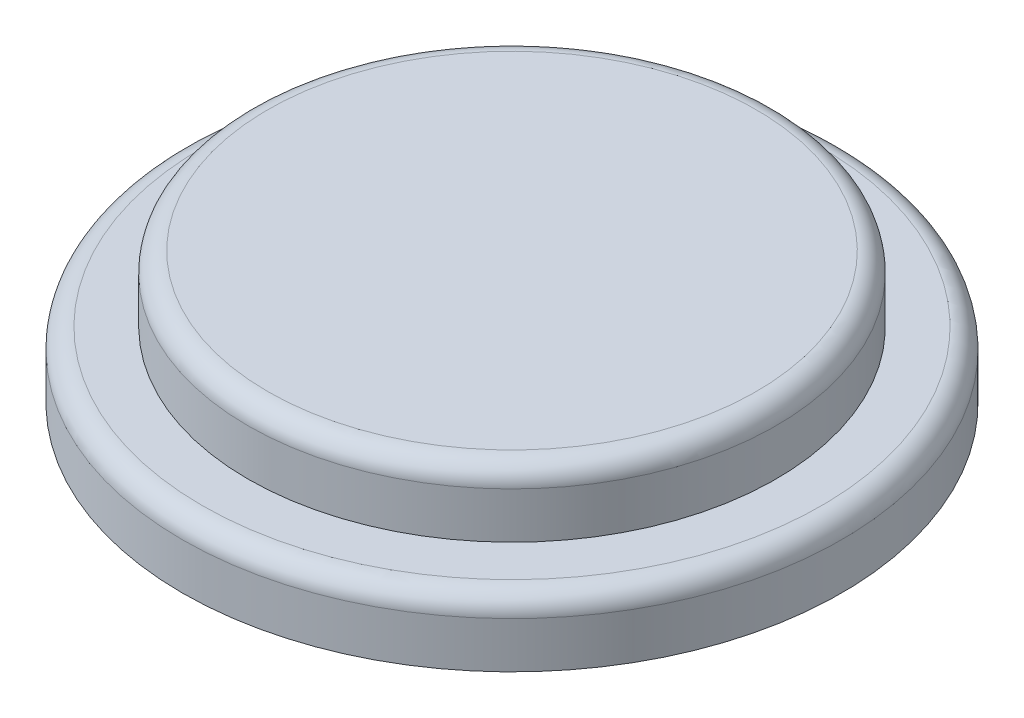
SolidWorks part; units mm, degrees
ref_plane "Front Plane" through (0, 0, 0) normal (0, 0, 1) x (1, 0, 0)
ref_plane "Top Plane" through (0, 0, 0) normal (0, 1, 0) x (1, 0, 0)
ref_plane "Right Plane" through (0, 0, 0) normal (1, 0, 0) x (0, 0, -1)
sketch "Sketch1" plane through (0, 0, 0) normal (0, 1, 0) x (1, 0, 0)
  circle A0 centre (0, 0) radius 12.7
  dimension "D1" = 25.4
extrude "Boss-Extrude1" add sketch "Sketch1" along normal blind 2.54
sketch "Sketch2" plane through (0, 2.54, 0) normal (0, 1, 0) x (1, 0, 0)
  circle A0 centre (0, 0) radius 10.1722
extrude "Boss-Extrude2" add sketch "Sketch2" along normal blind 2.54
fillet "Fillet1" radius 0.762 1 edges at (0, 2.54, 12.7)
fillet "Fillet2" radius 0.762 1 edges at (0, 5.08, 10.1722)
